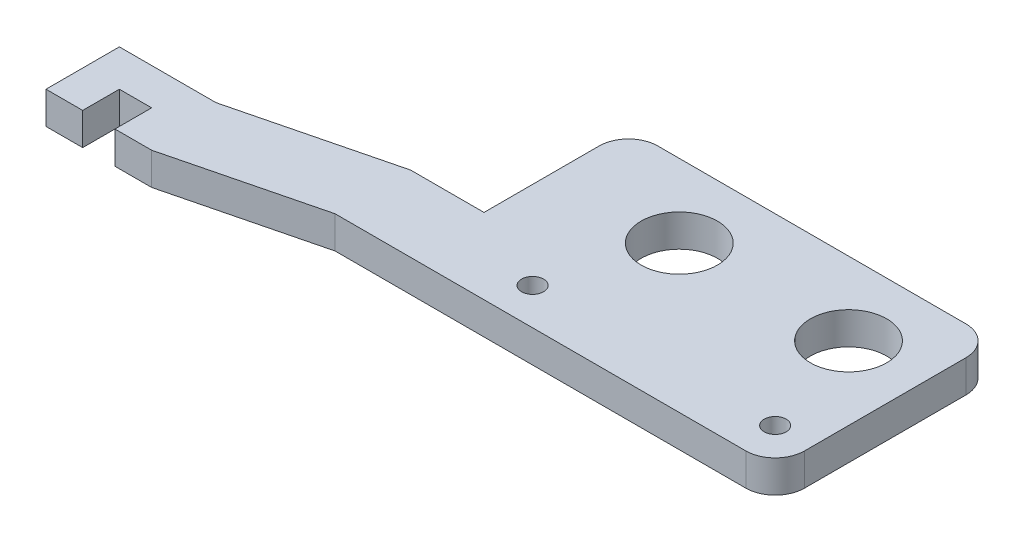
SolidWorks part; units mm, degrees
ref_plane "Front Plane" through (0, 0, 0) normal (0, 0, 1) x (1, 0, 0)
ref_plane "Top Plane" through (0, 0, 0) normal (0, 1, 0) x (1, 0, 0)
ref_plane "Right Plane" through (0, 0, 0) normal (1, 0, 0) x (0, 0, -1)
sketch "Sketch1" plane through (0, 0, 0) normal (0, 1, 0) x (1, 0, 0)
  line L0 (59.944, 0) -> (21.844, 0)
  line L1 (21.844, 0) -> (9.144, -3.175)
  line L2 (9.144, -3.175) -> (5.969, -3.175)
  line L3 (5.969, -3.175) -> (5.969, 0)
  line L4 (5.969, 0) -> (3.175, 0)
  line L5 (3.175, 0) -> (3.175, -3.175)
  line L6 (3.175, -3.175) -> (0, -3.175)
  line L7 (0, -3.175) -> (0, 3.175)
  line L8 (0, 3.175) -> (8.3623, 3.175)
  line L9 (8.3623, 3.175) -> (21.844, 6.5454)
  line L10 (21.844, 6.5454) -> (28.194, 6.5454)
  line L11 (59.944, 19.05) -> (59.944, 0)
  line L12 (28.194, 19.05) -> (59.944, 19.05)
  line L13 (28.194, 6.5454) -> (28.194, 19.05)
  dimension "D1" = 19.05
  dimension "D2" = 3.175
  dimension "D3" = 2.794
  dimension "D4" = 3.175
  dimension "D5" = 3.175
  dimension "D6" = 12.7
  dimension "D7" = 6.35
  dimension "D8" = 6.35
  dimension "D9" = 31.75
  dimension "D10" = 6.35
extrude "Boss-Extrude1" add sketch "Sketch1" along normal blind 2.794
sketch "Sketch2" plane through (0, 2.794, 0) normal (0, 1, 0) x (1, 0, 0)
  line L0 (35.769, 3.175) -> (56.769, 3.175) construction
  line L1 (59.944, 0) -> (59.944, 19.05) construction
  line L2 (21.844, 0) -> (59.944, 0) construction
  line L3 (38.944, 12.7) -> (53.594, 12.7) construction
  line L4 (46.269, 12.7) -> (46.269, 3.175) construction
  line L5 (59.944, 19.05) -> (28.194, 19.05) construction
  line L6 (59.944, 0) -> (59.944, 19.05) construction
  circle A0 centre (56.769, 3.175) radius 0.9525
  circle A1 centre (35.769, 3.175) radius 0.9525
  circle A2 centre (53.594, 12.7) radius 3.302
  circle A3 centre (38.944, 12.7) radius 3.302
  dimension "D1" = 1.905
  dimension "D5" = 6.604
  dimension "D2" = 21
  dimension "D3" = 3.175
  dimension "D4" = 3.175
  dimension "D6" = 6.35
  dimension "D7" = 6.35
extrude "Cut-Extrude1" cut sketch "Sketch2" against normal through all
fillet "Fillet2" radius 2.54 3 edges at (59.944, 1.397, 0) (59.944, 1.397, -19.05) (28.194, 1.397, -19.05)
equation "\"D1@Boss-Extrude1\"=\"thick@assy.sldasm\""
equation "\"D3@Sketch1\"=\"thick@assy.sldasm\""
